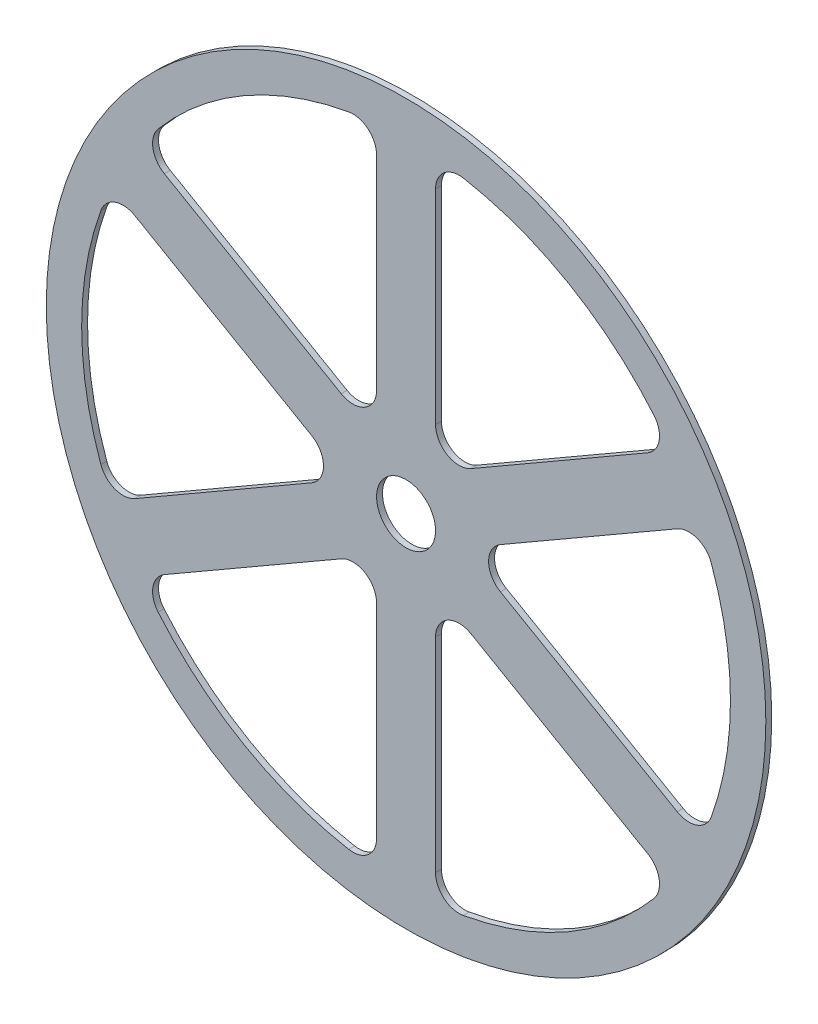
SolidWorks part; units mm, degrees
ref_plane "Front Plane" through (0, 0, 0) normal (0, 0, 1) x (1, 0, 0)
ref_plane "Top Plane" through (0, 0, 0) normal (0, 1, 0) x (1, 0, 0)
ref_plane "Right Plane" through (0, 0, 0) normal (1, 0, 0) x (0, 0, -1)
sketch "Sketch1" plane through (0, 0, 0) normal (0, 0, 1) x (1, 0, 0)
  circle A0 centre (0, 0) radius 193.675
  circle A1 centre (0, 0) radius 15.875
  circle A2 centre (0, 0) radius 34.925
  circle A3 centre (0, 0) radius 174.625
  dimension "D1" = 387.35
  dimension "D2" = 31.75
  dimension "D3" = 19.05
  dimension "D4" = 19.05
extrude "Boss-Extrude1" add sketch "Sketch1" along normal blind 3.175 contours A0 A3 | A2 A1
sketch "Sketch2" plane through (0, 0, 3.175) normal (0, 0, 1) x (1, 0, 0)
  line L0 (0, 0) -> (0, 174.625) construction
  line L1 (15.875, 49.4934) -> (15.875, 159.3837)
  line L2 (-15.875, 49.4934) -> (-15.875, 159.3837)
  line L3 (15.875, 0) -> (15.875, 174.625) construction
  line L4 (-15.875, 0) -> (-15.875, 174.625) construction
  line L5 (34.925, 38.4948) -> (130.0929, 93.44)
  line L6 (50.8, 10.9985) -> (145.9679, 65.9437)
  line L7 (50.8, -10.9985) -> (145.9679, -65.9437)
  line L8 (34.925, -38.4948) -> (130.0929, -93.44)
  line L9 (15.875, -49.4934) -> (15.875, -159.3837)
  line L10 (-15.875, -49.4934) -> (-15.875, -159.3837)
  line L11 (-34.925, -38.4948) -> (-130.0929, -93.44)
  line L12 (-50.8, -10.9985) -> (-145.9679, -65.9437)
  line L13 (-50.8, 10.9985) -> (-145.9679, 65.9437)
  line L14 (-34.925, 38.4948) -> (-130.0929, 93.44)
  circle A0 centre (0, 0) radius 174.625 construction
  arc A1 (-50.0133, 167.3098) -> (-30.8162, 171.8844) centre (0, 0) cw construction
  arc A2 (30.8162, 171.8844) -> (68.6917, 160.547) centre (0, 0) cw construction
  arc A3 (-30.8162, 171.8844) -> (-15.875, 159.3837) centre (-28.575, 159.3837) cw
  arc A4 (15.875, 159.3837) -> (30.8162, 171.8844) centre (28.575, 159.3837) cw
  arc A5 (-50.8, -10.9985) -> (-50.8, 10.9985) centre (-57.15, 0) ccw
  arc A7 (-15.875, -49.4934) -> (-34.925, -38.4948) centre (-28.575, -49.4934) ccw
  arc A11 (-30.8162, 171.8844) -> (30.8162, 171.8844) centre (0, 0) cw
  arc A14 (133.4482, 112.6298) -> (130.0929, 93.44) centre (123.7429, 104.4385) cw
  arc A15 (133.4482, 112.6298) -> (164.2644, 59.2546) centre (0, 0) cw
  arc A16 (145.9679, 65.9437) -> (164.2644, 59.2546) centre (152.3179, 54.9452) cw
  arc A20 (164.2644, -59.2546) -> (145.9679, -65.9437) centre (152.3179, -54.9452) cw
  arc A21 (164.2644, -59.2546) -> (133.4482, -112.6298) centre (0, 0) cw
  arc A22 (130.0929, -93.44) -> (133.4482, -112.6298) centre (123.7429, -104.4385) cw
  arc A26 (30.8162, -171.8844) -> (15.875, -159.3837) centre (28.575, -159.3837) cw
  arc A27 (30.8162, -171.8844) -> (-30.8162, -171.8844) centre (0, 0) cw
  arc A28 (-15.875, -159.3837) -> (-30.8162, -171.8844) centre (-28.575, -159.3837) cw
  arc A32 (-133.4482, -112.6298) -> (-130.0929, -93.44) centre (-123.7429, -104.4385) cw
  arc A33 (-133.4482, -112.6298) -> (-164.2644, -59.2546) centre (0, 0) cw
  arc A34 (-145.9679, -65.9437) -> (-164.2644, -59.2546) centre (-152.3179, -54.9452) cw
  arc A38 (-164.2644, 59.2546) -> (-145.9679, 65.9437) centre (-152.3179, 54.9452) cw
  arc A39 (-164.2644, 59.2546) -> (-133.4482, 112.6298) centre (0, 0) cw
  arc A40 (-130.0929, 93.44) -> (-133.4482, 112.6298) centre (-123.7429, 104.4385) cw
  circle A42 centre (0, 0) radius 15.875 construction
  arc A43 (34.925, -38.4948) -> (15.875, -49.4934) centre (28.575, -49.4934) ccw
  arc A44 (50.8, 10.9985) -> (50.8, -10.9985) centre (57.15, 0) ccw
  arc A45 (15.875, 49.4934) -> (34.925, 38.4948) centre (28.575, 49.4934) ccw
  arc A46 (-15.875, 49.4934) -> (-34.925, 38.4948) centre (-28.575, 49.4934) cw
  circle A47 centre (0, 0) radius 15.875
  point P5 (0, 0)
  point P20 (15.875, 173.9019)
  point P95 (0, 0)
  dimension "D3" = 12.7
  dimension "D4" = 12.7
  dimension "D1" = 15.875
  dimension "D2" = 15.875
  dimension "D5" = 6
extrude "Boss-Extrude2" add sketch "Sketch2" against normal blind 3.175
